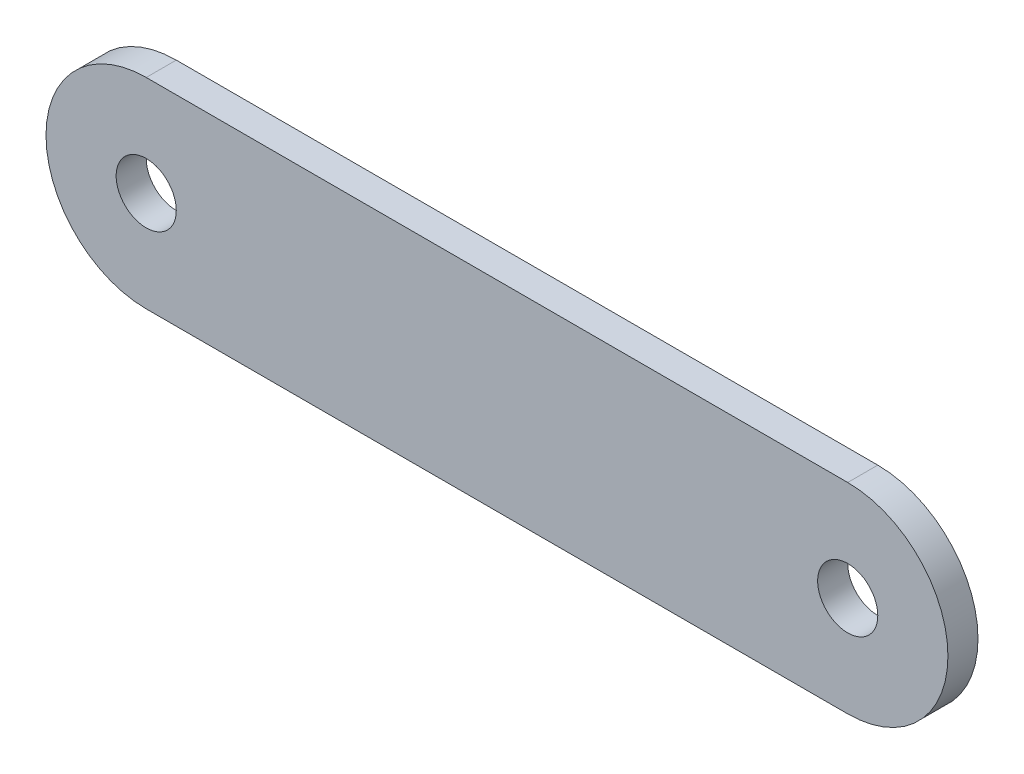
SolidWorks part; units mm, degrees
ref_plane "前视基准面" through (0, 0, 0) normal (0, 0, 1) x (1, 0, 0)
ref_plane "上视基准面" through (0, 0, 0) normal (0, 1, 0) x (1, 0, 0)
ref_plane "右视基准面" through (0, 0, 0) normal (1, 0, 0) x (0, 0, -1)
sketch "草图1" plane through (0, 0, 0) normal (0, 0, 1) x (1, 0, 0)
  line L0 (0, 0) -> (70, 0) construction
  line L1 (0, 10) -> (70, 10)
  line L2 (0, -10) -> (70, -10)
  circle A0 centre (0, 0) radius 3
  circle A1 centre (70, 0) radius 3
  arc A2 (0, 10) -> (0, -10) centre (0, 0) ccw
  arc A3 (70, -10) -> (70, 10) centre (70, 0) ccw
  point P5 (35, 0)
  dimension "D2" = 6
  dimension "D3" = 6
  dimension "D4" = 10
  dimension "D1" = 70
extrude "凸台-拉伸1" add sketch "草图1" along normal blind 3
